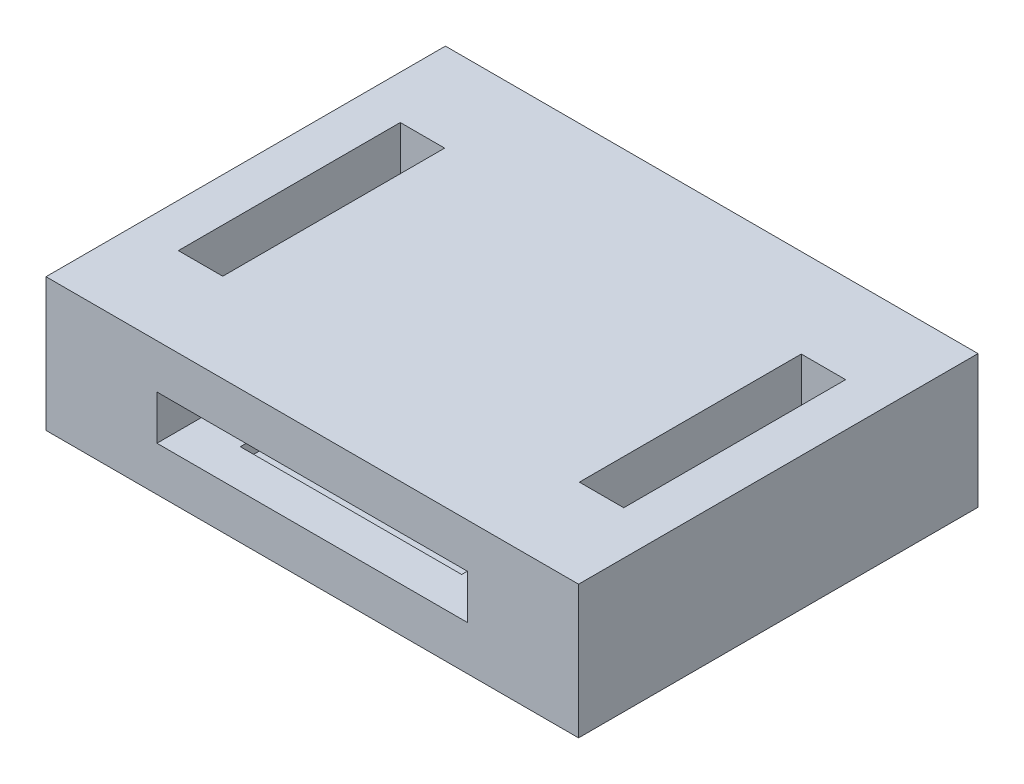
SolidWorks part; units mm, degrees
ref_plane "Front Plane" through (0, 0, 0) normal (0, 0, 1) x (1, 0, 0)
ref_plane "Top Plane" through (0, 0, 0) normal (0, 1, 0) x (1, 0, 0)
ref_plane "Right Plane" through (0, 0, 0) normal (1, 0, 0) x (0, 0, -1)
sketch "Sketch1" plane through (0, 0, 0) normal (0, 1, 0) x (1, 0, 0)
  line L0 (-15.24, 0) -> (-11.4749, 0) construction
  line L1 (-15.24, -11.43) -> (15.24, -11.43)
  line L2 (-15.24, -11.43) -> (-15.24, 11.43)
  line L3 (-15.24, 11.43) -> (15.24, 11.43)
  line L4 (15.24, -11.43) -> (15.24, 11.43)
  line L5 (-15.24, -11.43) -> (15.24, 11.43) construction
  line L6 (-15.24, 11.43) -> (15.24, -11.43) construction
  line L7 (0, -1000) -> (0, 49000) construction
  line L8 (-10.2049, -6.35) -> (-12.7449, -6.35)
  line L9 (-10.2049, -6.35) -> (-10.2049, 6.35)
  line L10 (-10.2049, 6.35) -> (-12.7449, 6.35)
  line L11 (-12.7449, -6.35) -> (-12.7449, 6.35)
  line L12 (-10.2049, -6.35) -> (-12.7449, 6.35) construction
  line L13 (-10.2049, 6.35) -> (-12.7449, -6.35) construction
  line L14 (10.2049, 6.35) -> (12.7449, 6.35)
  line L15 (12.7449, -6.35) -> (12.7449, 6.35)
  line L16 (10.2049, -6.35) -> (12.7449, -6.35)
  line L17 (10.2049, -6.35) -> (10.2049, 6.35)
  point P0 (0, 0)
  dimension "D1" = 22.86
  dimension "D2" = 30.48
  dimension "D3" = 12.7
  dimension "D4" = 2.54
  dimension "D5" = 2.4951
extrude "Boss-Extrude2" add sketch "Sketch1" along normal blind 2.54
sketch "Sketch3" plane through (0, 2.54, 0) normal (0, 1, 0) x (1, 0, 0)
  line L0 (0, 11.43) -> (0, 1.27) construction
  line L1 (15.24, 11.43) -> (-15.24, 11.43) construction
  line L2 (5.3189, 1.27) -> (-5.3189, 1.27) construction
  circle A0 centre (-5.3189, 1.27) radius 1.016
  circle A1 centre (5.3189, 1.27) radius 1.016
extrude "Boss-Extrude3" add sketch "Sketch3" along normal blind 2.54
ref_plane "Plane2" through (0, 5.08, 0) normal (0, 1, 0) x (1, 0, 0)
sketch "Sketch4" plane through (0, 5.08, 0) normal (0, 1, 0) x (1, 0, 0)
  line L0 (10.2049, 6.35) -> (10.2049, -6.35) construction
  line L1 (-15.24, 11.43) -> (15.24, 11.43)
  line L2 (-15.24, 11.43) -> (-15.24, -11.43)
  line L3 (-15.24, -11.43) -> (15.24, -11.43)
  line L4 (15.24, 11.43) -> (15.24, -11.43)
  line L5 (-12.7449, 6.35) -> (-10.2049, 6.35)
  line L6 (-12.7449, 6.35) -> (-12.7449, -6.35)
  line L7 (-12.7449, -6.35) -> (-10.2049, -6.35)
  line L8 (-10.2049, 6.35) -> (-10.2049, -6.35)
  line L9 (10.2049, 6.35) -> (12.7449, 6.35)
  line L10 (10.2049, 6.35) -> (10.2049, -6.35)
  line L11 (10.2049, -6.35) -> (12.7449, -6.35)
  line L12 (12.7449, 6.35) -> (12.7449, -6.35)
sketch "Sketch5" plane through (0, 2.54, 0) normal (0, 1, 0) x (1, 0, 0)
  line L0 (-15.24, -11.43) -> (-15.24, 11.43)
  line L1 (15.24, 11.43) -> (-15.24, 11.43) construction
  line L2 (-15.24, 11.43) -> (-15.24, -11.43) construction
  line L5 (-15.24, -11.43) -> (15.24, -11.43) construction
  line L8 (-15.24, -11.43) -> (-8.89, -11.43)
  line L11 (-8.89, -11.43) -> (-8.89, 6.35)
  line L12 (-8.89, 6.35) -> (8.89, 6.35)
  line L13 (8.89, 6.35) -> (8.89, -11.43)
  line L14 (-15.24, -11.43) -> (15.24, -11.43) construction
  line L15 (8.89, -11.43) -> (15.24, -11.43)
  line L16 (15.24, -11.43) -> (15.24, 11.43)
  line L17 (15.24, 11.43) -> (-15.24, 11.43)
  line L21 (-12.7449, 6.35) -> (-10.2049, 6.35)
  line L22 (-12.7449, 6.35) -> (-12.7449, -6.35)
  line L23 (-12.7449, -6.35) -> (-10.2049, -6.35)
  line L24 (-10.2049, 6.35) -> (-10.2049, -6.35)
  line L25 (10.2049, 6.35) -> (12.7449, 6.35)
  line L26 (10.2049, 6.35) -> (10.2049, -6.35)
  line L27 (10.2049, -6.35) -> (12.7449, -6.35)
  line L28 (12.7449, 6.35) -> (12.7449, -6.35)
  dimension "D1" = 6.35
  dimension "D2" = 17.78
  dimension "D3" = 17.78
extrude "Boss-Extrude6" add sketch "Sketch4" along normal blind 2.54
extrude "Boss-Extrude7" add sketch "Sketch5" along normal up to surface (2.54 mm away) up to face at (-5.3189, 5.08, -0.254)
sketch "Sketch6" plane through (0, 2.54, 0) normal (0, 1, 0) x (1, 0, 0)
  line L0 (-6.3349, -998.73) -> (-6.3349, 49001.27) construction
  line L1 (6.3349, -998.73) -> (6.3349, 49001.27) construction
  line L3 (-6.3349, -1.1192) -> (6.3349, -1.1192)
  line L4 (-6.3349, -1.1192) -> (-6.3349, -9.2155)
  line L5 (-6.3349, -9.2155) -> (6.3349, -9.2155)
  line L6 (6.3349, -1.1192) -> (6.3349, -9.2155)
extrude "Cut-Extrude1" cut sketch "Sketch6" against normal blind 0.762
